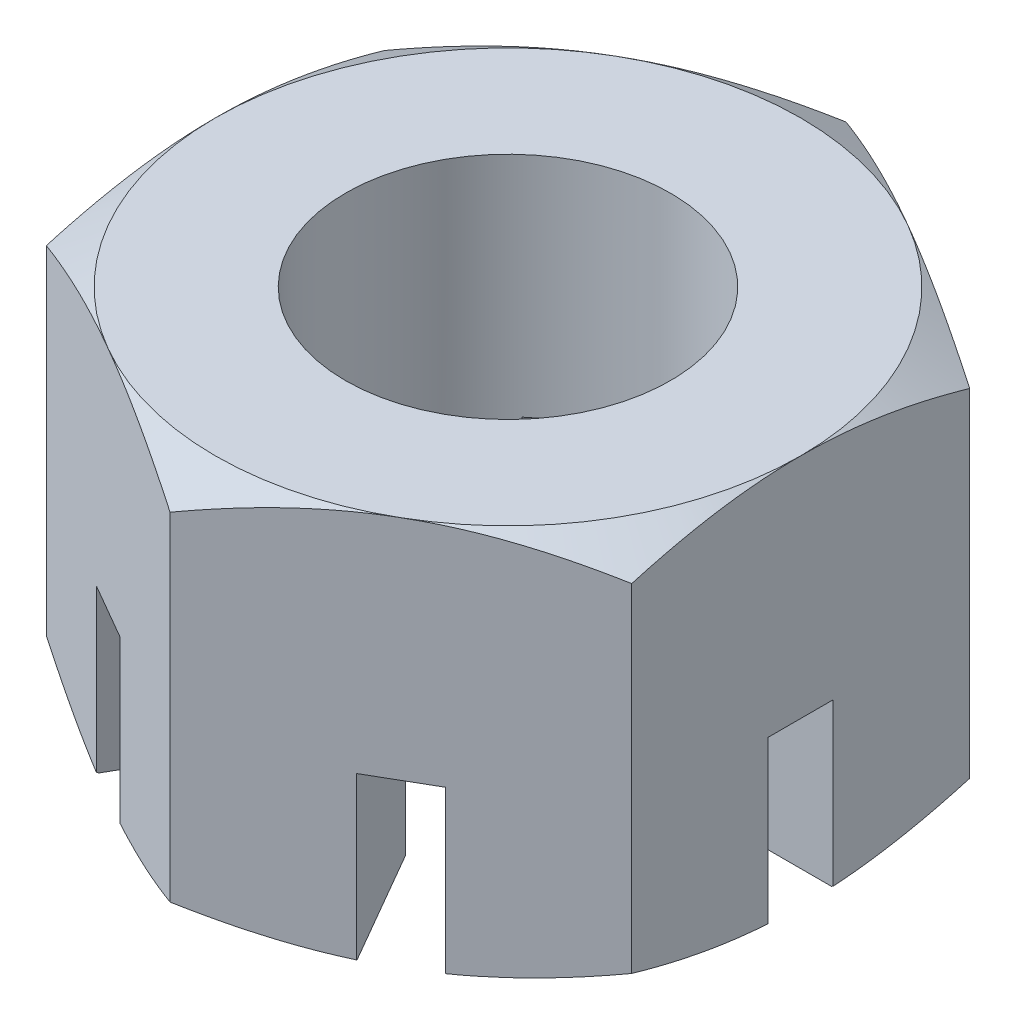
SolidWorks part; units mm, degrees
ref_plane "Front Plane" through (0, 0, 0) normal (0, 0, 1) x (1, 0, 0)
ref_plane "Top Plane" through (0, 0, 0) normal (0, 1, 0) x (1, 0, 0)
ref_plane "Right Plane" through (0, 0, 0) normal (1, 0, 0) x (0, 0, -1)
sketch "Sketch2" plane through (0, 0, 0) normal (0, 1, 0) x (1, 0, 0)
  line L1 (0, 52) -> (-45.0333, 26)
  line L2 (-45.0333, 26) -> (-45.0333, -26)
  line L3 (-45.0333, -26) -> (0, -52)
  line L4 (0, -52) -> (45.0333, -26)
  line L5 (45.0333, -26) -> (45.0333, 26)
  line L6 (45.0333, 26) -> (0, 52)
  circle A0 centre (0, 0) radius 45.0333 construction
  circle A1 centre (0, 0) radius 25
  dimension "D2" = 50
  dimension "D1" = 104
extrude "Boss-Extrude1" add sketch "Sketch2" along normal mid plane 60
sketch "Sketch3" plane through (0, 30, 0) normal (0, 1, 0) x (1, 0, 0)
  circle A0 centre (0, 0) radius 45.0333
extrude "Cut-Extrude1" cut sketch "Sketch3" against normal blind 60 draft 60 flip side to cut
sketch "Sketch4" plane through (0, -30, 0) normal (0, -1, 0) x (1, 0, 0)
  circle A0 centre (0, 0) radius 45.0333
extrude "Cut-Extrude2" cut sketch "Sketch4" against normal blind 60 draft 60 flip side to cut
sketch "Sketch5" plane through (0, -30, 0) normal (0, -1, 0) x (1, 0, 0)
  line L0 (19.7549, 0) -> (56.7557, 0) construction
  line L1 (19.7549, 5) -> (19.7549, -5)
  line L26 (47.6908, 5) -> (47.6908, -5)
  line L58 (19.7549, 5) -> (47.6908, 5)
  line L59 (47.6908, -5) -> (19.7549, -5)
  line L60 (19.5153, -43.8014) -> (5.5473, -19.6082)
  line L61 (14.2076, -14.6082) -> (5.5473, -19.6082)
  line L62 (14.2076, -14.6082) -> (28.1755, -38.8014)
  line L63 (28.1755, -38.8014) -> (19.5153, -43.8014)
  line L64 (-28.1755, -38.8014) -> (-14.2076, -14.6082)
  line L65 (-5.5473, -19.6082) -> (-14.2076, -14.6082)
  line L66 (-5.5473, -19.6082) -> (-19.5153, -43.8014)
  line L67 (-19.5153, -43.8014) -> (-28.1755, -38.8014)
  line L68 (-47.6908, 5) -> (-19.7549, 5)
  line L69 (-19.7549, -5) -> (-19.7549, 5)
  line L70 (-19.7549, -5) -> (-47.6908, -5)
  line L71 (-47.6908, -5) -> (-47.6908, 5)
  line L72 (-19.5153, 43.8014) -> (-5.5473, 19.6082)
  line L73 (-14.2076, 14.6082) -> (-5.5473, 19.6082)
  line L74 (-14.2076, 14.6082) -> (-28.1755, 38.8014)
  line L75 (-28.1755, 38.8014) -> (-19.5153, 43.8014)
  line L76 (28.1755, 38.8014) -> (14.2076, 14.6082)
  line L77 (5.5473, 19.6082) -> (14.2076, 14.6082)
  line L78 (5.5473, 19.6082) -> (19.5153, 43.8014)
  line L79 (19.5153, 43.8014) -> (28.1755, 38.8014)
  point P31 (0, 0)
  point P37 (0, 0)
  point P51 (0, 0)
  dimension "D1" = 6
  dimension "D3" = 10
extrude "Cut-Extrude4" cut sketch "Sketch5" against normal blind 25
